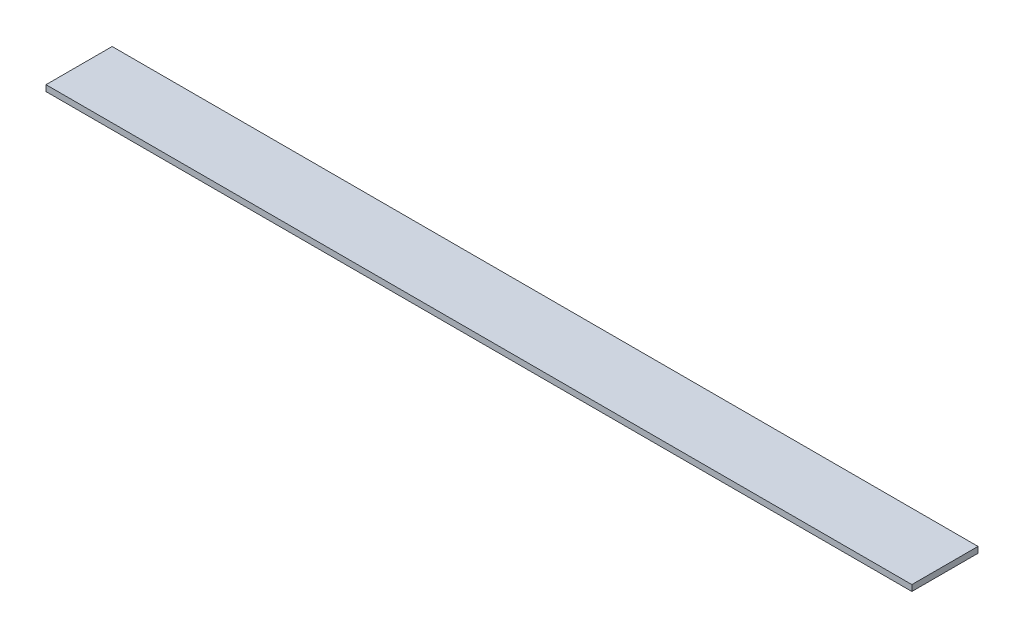
SolidWorks part; units mm, degrees
ref_plane "Front Plane" through (0, 0, 0) normal (0, 0, 1) x (1, 0, 0)
ref_plane "Top Plane" through (0, 0, 0) normal (0, 1, 0) x (1, 0, 0)
ref_plane "Right Plane" through (0, 0, 0) normal (1, 0, 0) x (0, 0, -1)
sketch "Sketch1" plane through (0, 0, 0) normal (0, 1, 0) x (1, 0, 0)
  line L1 (-39.5348, 106.0084) -> (1789.2652, 106.0084)
  line L2 (-39.5348, 106.0084) -> (-39.5348, -33.6916)
  line L3 (-39.5348, -33.6916) -> (1789.2652, -33.6916)
  line L4 (1789.2652, 106.0084) -> (1789.2652, -33.6916)
extrude "Boss-Extrude1" add sketch "Sketch1" along normal blind 12.7
